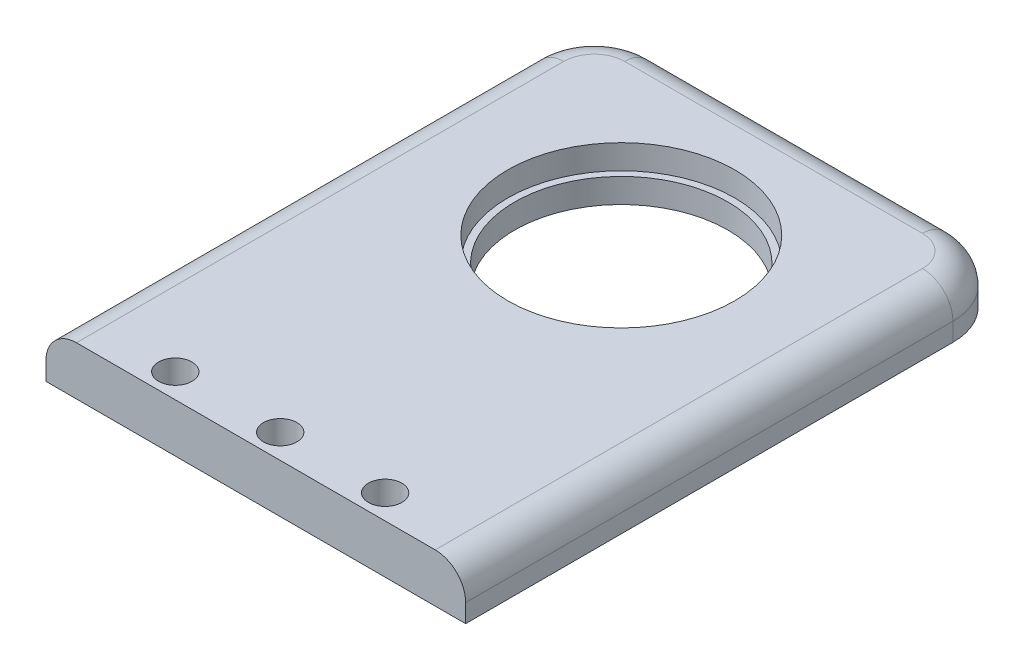
SolidWorks part; units mm, degrees
ref_plane "Front Plane" through (0, 0, 0) normal (0, 0, 1) x (1, 0, 0)
ref_plane "Top Plane" through (0, 0, 0) normal (0, 1, 0) x (1, 0, 0)
ref_plane "Right Plane" through (0, 0, 0) normal (1, 0, 0) x (0, 0, -1)
sketch "Sketch1" plane through (0, 0, 0) normal (0, 1, 0) x (1, 0, 0)
  line L0 (-33.7277, -40) -> (35.1723, -40)
  line L1 (-33.7277, -40) -> (-33.7277, 50)
  line L2 (-33.7277, 50) -> (35.1723, 50)
  line L3 (35.1723, -40) -> (35.1723, 50)
  circle A0 centre (0.7223, 20) radius 18.63
  circle A1 centre (0.7223, -36) radius 2.75
  circle A2 centre (-16.5027, -36) radius 2.75
  circle A3 centre (17.9473, -36) radius 2.75
  dimension "D1" = 30
  dimension "D2" = 68.9
  dimension "D3" = 34.45
  dimension "D4" = 34.45
  dimension "D5" = 17.225
  dimension "D6" = 17.225
  dimension "D7" = 4
  dimension "D8" = 90
  dimension "D9" = 4
extrude "Boss-Extrude1" add sketch "Sketch1" along normal blind 8
fillet "Fillet1" radius 10 2 edges at (35.1723, 4, -50) (-33.7277, 4, -50)
fillet "Fillet2" radius 5 5 edges at (32.2434, 8, -47.0711) (0.7223, 8, -50) (-30.7987, 8, -47.0711) (35.1723, 8, 0) (-33.7277, 8, 0)
sketch "Sketch2" plane through (0, 0, 0) normal (0, -1, 0) x (1, 0, 0)
  circle A0 centre (0.7223, -20) radius 17.5
  circle A1 centre (0.7223, -20) radius 18.63
extrude "Boss-Extrude2" add sketch "Sketch2" against normal blind 4
